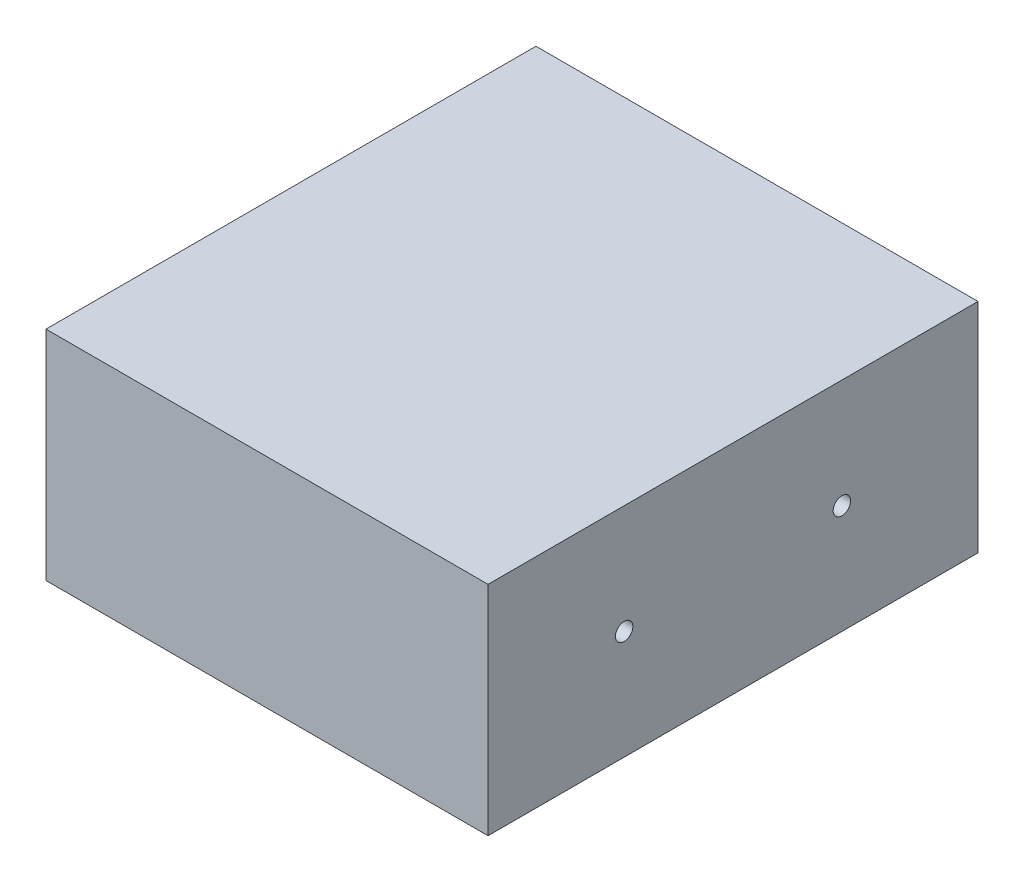
SolidWorks part; units mm, degrees
ref_plane "前视基准面" through (0, 0, 0) normal (0, 0, 1) x (1, 0, 0)
ref_plane "上视基准面" through (0, 0, 0) normal (0, 1, 0) x (1, 0, 0)
ref_plane "右视基准面" through (0, 0, 0) normal (1, 0, 0) x (0, 0, -1)
sketch "草图1" plane through (0, 0, 0) normal (0, 1, 0) x (1, 0, 0)
  line L1 (-20.3, -22.5) -> (20.3, -22.5)
  line L2 (-20.3, -22.5) -> (-20.3, 22.5)
  line L3 (-20.3, 22.5) -> (20.3, 22.5)
  line L4 (20.3, -22.5) -> (20.3, 22.5)
  line L5 (-20.3, -22.5) -> (20.3, 22.5) construction
  line L6 (-20.3, 22.5) -> (20.3, -22.5) construction
  point P0 (0, 0)
  dimension "D1" = 40.6
  dimension "D2" = 45
extrude "凸台-拉伸1" add sketch "草图1" along normal blind 20
hole_wizard "M2 螺纹孔的螺纹孔钻头1" positions "草图4" profile "草图3" hole size "M2" standard "GB"
sketch "草图4" plane through (20.3, 0, 0) normal (1, 0, 0) x (0, 0, -1)
  line L0 (-22.5, 0) -> (22.5, 0) construction
  point P0 (-10, 10)
  point P2 (10, 10)
  point P12 (0, 0)
  point P13 (0, 0)
  dimension "D1" = 10
  dimension "D2" = 10
  dimension "D3" = 10
  dimension "D4" = 10
sketch "草图3" plane through (20.3, 10, 10) normal (0, 1, 0) x (0, 0, -1)
  line L0 (0, 0) -> (0, 8.4807)
  line L1 (0, 8.4807) -> (0.8, 8)
  line L2 (0.8, 8) -> (0.8, 0)
  line L5 (0.8, 0) -> (0, 0)
  line L10 (0, 8.4807) -> (-0.8, 8) construction
  line L11 (0, -6.35) -> (0, 107.95) construction
  dimension "孔直径" = 1.6
  dimension "孔深度" = 8
  dimension "导头角度" = 118
mirror "镜向1" about plane through (0, 0, 0) normal (1, 0, 0) of "M2 螺纹孔的螺纹孔钻头1"
